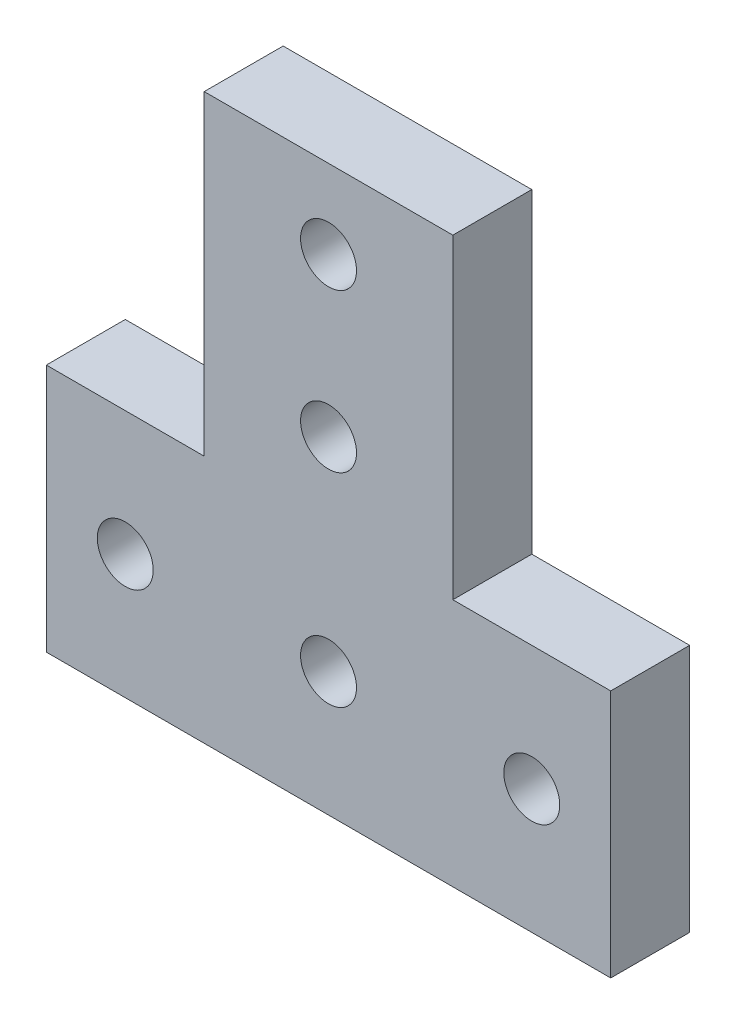
SolidWorks part; units mm, degrees
ref_plane "Front Plane" through (0, 0, 0) normal (0, 0, 1) x (1, 0, 0)
ref_plane "Top Plane" through (0, 0, 0) normal (0, 1, 0) x (1, 0, 0)
ref_plane "Right Plane" through (0, 0, 0) normal (1, 0, 0) x (0, 0, -1)
sketch "Sketch1" plane through (0, 0, 0) normal (0, 0, 1) x (1, 0, 0)
  line L0 (-16.35, -12.7) -> (-16.35, -32.7)
  line L1 (-10, -12.7) -> (10, -12.7)
  line L2 (-10, -12.7) -> (-10, 12.7)
  line L3 (-10, 12.7) -> (10, 12.7)
  line L4 (10, -12.7) -> (10, 12.7)
  line L5 (-10, -12.7) -> (10, 12.7) construction
  line L6 (-10, 12.7) -> (10, -12.7) construction
  line L7 (-10, -12.7) -> (10, -12.7)
  line L8 (-10, -12.7) -> (-10, -32.7)
  line L9 (-10, -32.7) -> (10, -32.7)
  line L10 (10, -12.7) -> (10, -32.7)
  line L11 (10, -12.7) -> (22.7, -12.7)
  line L12 (10, -12.7) -> (10, -32.7)
  line L13 (10, -32.7) -> (22.7, -32.7)
  line L14 (22.7, -12.7) -> (22.7, -32.7)
  line L15 (-10, -12.7) -> (-22.7, -12.7)
  line L16 (-10, -12.7) -> (-10, -32.7)
  line L17 (-10, -32.7) -> (-22.7, -32.7)
  line L18 (-22.7, -12.7) -> (-22.7, -32.7)
  line L19 (16.35, -12.7) -> (16.35, -32.7)
  line L20 (10, -12.7) -> (-10, -32.7)
  line L21 (-10, 0) -> (10, 0)
  line L22 (0, -12.7) -> (0, 0)
  line L23 (0, 0) -> (0, 12.7)
  circle A0 centre (0, 6.35) radius 2.25
  circle A1 centre (0, -6.35) radius 2.25
  circle A2 centre (0, -22.7) radius 2.25
  circle A3 centre (16.35, -22.7) radius 2.25
  circle A4 centre (-16.35, -22.7) radius 2.25
  point P0 (0, 0)
  dimension "D6" = 4.5
  dimension "D1" = 20
  dimension "D2" = 25.4
  dimension "D3" = 20
  dimension "D4" = 12.7
  dimension "D5" = 12.7
extrude "Boss-Extrude1" add sketch "Sketch1" along normal blind 6.35 contours A4 L0 L17 L8 L15 | A4 L0 L15 L18 L17 | A2 L20 L7 L1 L8 | A2 L20 L9 L10 | A3 L19 L11 L10 L13 | A3 L19 L13 L14 L11 | A1 L22 L7 L4 L21 | A1 L22 L21 L2 L1 | A0 L23 L3 L2 L21 | A0 L23 L21 L4 L3
